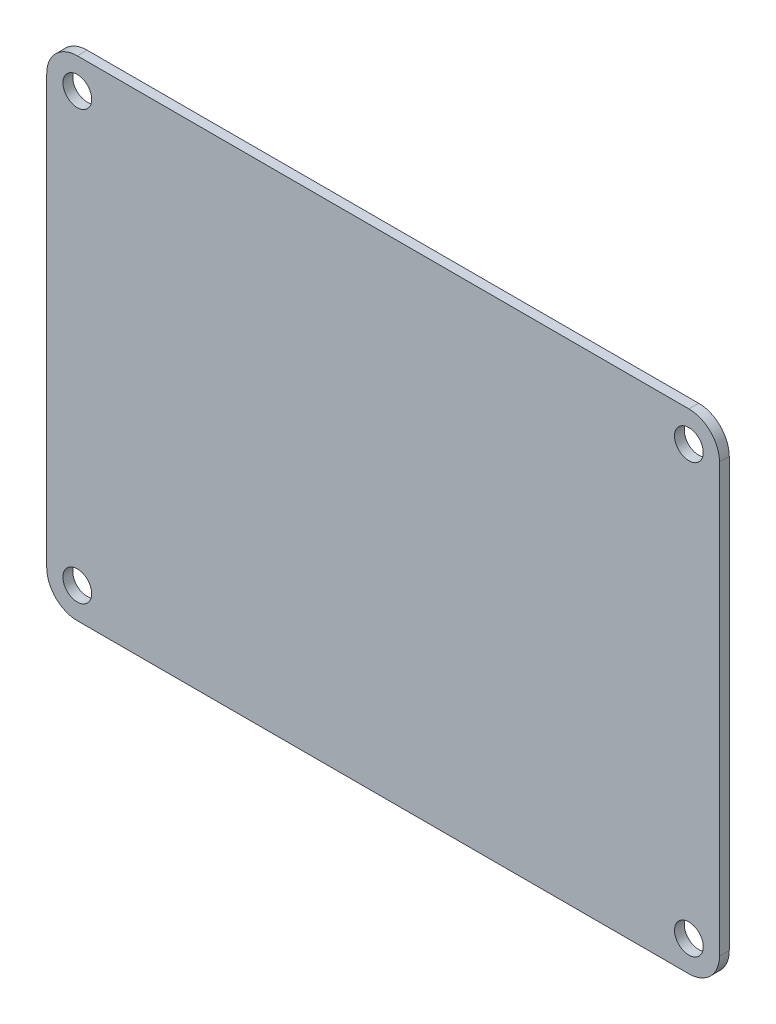
SolidWorks part; units mm, degrees
ref_plane "Front Plane" through (0, 0, 0) normal (0, 0, 1) x (1, 0, 0)
ref_plane "Top Plane" through (0, 0, 0) normal (0, 1, 0) x (1, 0, 0)
ref_plane "Right Plane" through (0, 0, 0) normal (1, 0, 0) x (0, 0, -1)
sketch "Sketch1" plane through (0, 0, 0) normal (0, 0, 1) x (1, 0, 0)
  line L1 (-50, -35) -> (50, -35) construction
  line L2 (-50, -35) -> (-50, 35) construction
  line L3 (-50, 35) -> (50, 35) construction
  line L4 (50, -35) -> (50, 35) construction
  line L5 (-50, -35) -> (50, 35) construction
  line L6 (-50, 35) -> (50, -35) construction
  line L7 (-55, -40) -> (55, -40)
  line L8 (-55, -40) -> (-55, 40)
  line L9 (-55, 40) -> (55, 40)
  line L10 (55, -40) -> (55, 40)
  line L11 (-55, -40) -> (55, 40) construction
  line L12 (-55, 40) -> (55, -40) construction
  circle A0 centre (50, 35) radius 2.35
  circle A1 centre (-50, 35) radius 2.35
  circle A2 centre (-50, -35) radius 2.35
  circle A3 centre (50, -35) radius 2.35
  point P0 (0, 0)
  point P10 (0, 0)
  dimension "D3" = 4.7
  dimension "D1" = 100
  dimension "D2" = 70
  dimension "D4" = 110
  dimension "D5" = 80
extrude "Boss-Extrude1" add sketch "Sketch1" along normal blind 1.6
fillet "Fillet1" radius 5 4 edges at (-55, 40, 0.8) (-55, -40, 0.8) (55, -40, 0.8) (55, 40, 0.8)
